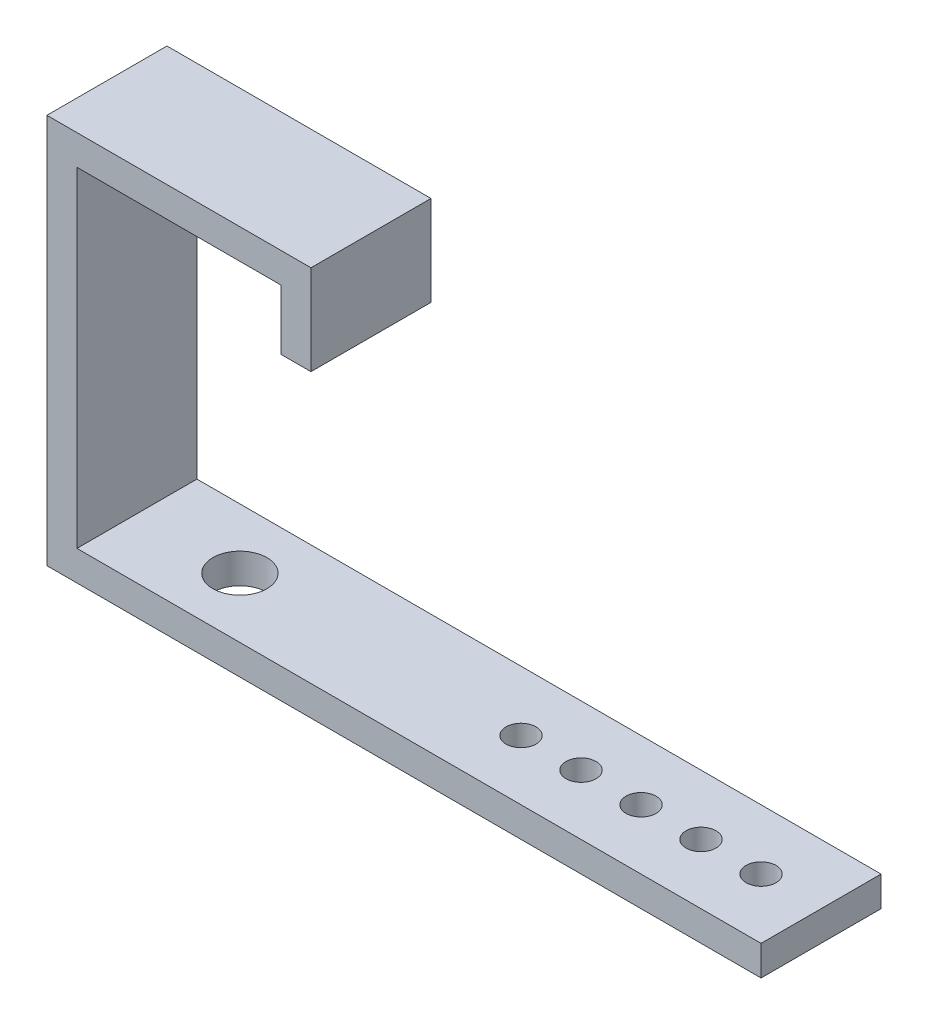
SolidWorks part; units mm, degrees
ref_plane "Plan de face" through (0, 0, 0) normal (0, 0, 1) x (1, 0, 0)
ref_plane "Plan de dessus" through (0, 0, 0) normal (0, 1, 0) x (1, 0, 0)
ref_plane "Plan de droite" through (0, 0, 0) normal (1, 0, 0) x (0, 0, -1)
sketch "Esquisse1" plane through (0, 0, 0) normal (0, 0, 1) x (1, 0, 0)
  line L1 (12.6256, 25.1526) -> (-21.3744, 25.1526)
  line L2 (12.6256, 25.1526) -> (12.6256, 20.1526)
  line L3 (12.6256, 20.1526) -> (-21.3744, 20.1526)
  line L4 (-21.3744, 25.1526) -> (-21.3744, 20.1526)
  line L5 (-21.3744, 25.1526) -> (-26.3744, 25.1526)
  line L6 (-21.3744, 25.1526) -> (-21.3744, -34.8474)
  line L7 (-21.3744, -34.8474) -> (-26.3744, -34.8474)
  line L8 (-26.3744, 25.1526) -> (-26.3744, -34.8474)
  line L9 (-26.3744, -34.8474) -> (12.6256, -34.8474)
  line L10 (-26.3744, -34.8474) -> (-26.3744, -39.8474)
  line L11 (-26.3744, -39.8474) -> (12.6256, -39.8474)
  line L12 (12.6256, -34.8474) -> (12.6256, -39.8474)
  line L13 (12.6256, 25.1526) -> (17.6256, 25.1526)
  line L14 (12.6256, 25.1526) -> (12.6256, 10.1526)
  line L15 (12.6256, 10.1526) -> (17.6256, 10.1526)
  line L16 (17.6256, 25.1526) -> (17.6256, 10.1526)
  dimension "D1" = 34
  dimension "D2" = 5
  dimension "D3" = 5
  dimension "D4" = 5
  dimension "D5" = 5
  dimension "D6" = 60
  dimension "D7" = 15
  dimension "D8" = 39
extrude "Boss.-Extru.1" add sketch "Esquisse1" along normal blind 20 contours L5 L8 L7 L6 L4 | L1 L4 L3 L2 | L16 L13 L2 L14 L15 | L12 L9 L7 L10 L11
sketch "Esquisse2" plane through (0, -39.8474, 0) normal (0, -1, 0) x (1, 0, 0)
  line L0 (-26.3744, 20) -> (12.6256, 20) construction
  circle A0 centre (-4.2199, 10) radius 4.5
  dimension "D1" = 9
  dimension "D2" = 10
extrude "Enlèv. mat.-Extru.1" cut sketch "Esquisse2" against normal up to surface (5 mm away) up to face at (-4.3744, -34.8474, 10)
sketch "Esquisse5" plane through (12.6256, 0, 0) normal (1, 0, 0) x (0, 0, -1)
  line L1 (-20, -34.8474) -> (0, -34.8474)
  line L2 (-20, -34.8474) -> (-20, -39.8474)
  line L3 (-20, -39.8474) -> (0, -39.8474)
  line L4 (0, -34.8474) -> (0, -39.8474)
extrude "Boss.-Extru.2" add sketch "Esquisse5" along normal blind 80
sketch "Esquisse6" plane through (0, -39.8474, 0) normal (0, -1, 0) x (1, 0, 0)
  line L0 (-26.3744, 20) -> (92.6256, 20) construction
  line L1 (92.6256, 20) -> (92.6256, 0) construction
  circle A0 centre (82.6256, 10) radius 2.5
  circle A1 centre (72.6256, 10) radius 2.5
  circle A2 centre (62.6256, 10) radius 2.5
  circle A3 centre (52.6256, 10) radius 2.5
  circle A4 centre (42.6256, 10) radius 2.5
  dimension "D1" = 10
  dimension "D3" = 5
  dimension "D2" = 10
  dimension "D4" = 5
extrude "Enlèv. mat.-Extru.2" cut sketch "Esquisse6" against normal up to surface (5 mm away) up to face at (-4.2199, -34.8474, 14.5)
